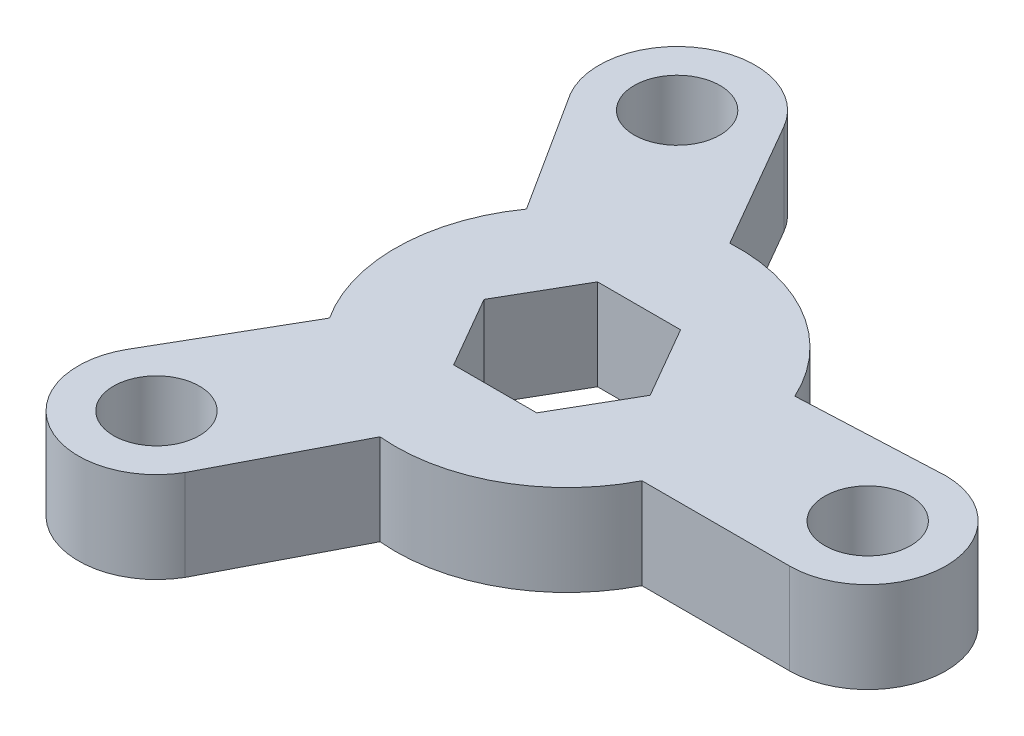
SolidWorks part; units mm, degrees
ref_plane "Front" through (0, 0, 0) normal (0, 0, 1) x (1, 0, 0)
ref_plane "Top" through (0, 0, 0) normal (0, 1, 0) x (1, 0, 0)
ref_plane "Right" through (0, 0, 0) normal (1, 0, 0) x (0, 0, -1)
sketch "Sketch1" plane through (0, 0, 0) normal (0, 1, 0) x (1, 0, 0)
  line L0 (2.5148, 0.2447) -> (13.0148, 0.2447)
  line L1 (2.5148, 0.2447) -> (-2.7352, 9.338)
  line L2 (2.5148, 0.2447) -> (-2.7352, -8.8486)
  line L3 (2.5148, 0.2447) -> (-2.7352, 9.338) construction
  line L10 (2.5148, 0.2447) -> (13.0148, 0.2447) construction
  line L11 (13.0148, -2.4841) -> (7.8583, -2.4841)
  line L12 (13.0148, 2.9736) -> (7.9691, 2.7447)
  line L13 (-5.0985, -7.4841) -> (-2.5203, -3.0185)
  line L14 (-0.372, -10.213) -> (1.9526, -5.7289)
  line L15 (-0.372, 10.7024) -> (2.2062, 6.2368)
  line L16 (-5.0985, 7.9736) -> (-2.3775, 3.7183)
  line L18 (1.0642, -2.2678) -> (3.9654, -2.2678)
  line L19 (3.9654, -2.2678) -> (5.4159, 0.2447)
  line L20 (5.4159, 0.2447) -> (3.9654, 2.7572)
  line L21 (3.9654, 2.7572) -> (1.0642, 2.7572)
  line L22 (1.0642, 2.7572) -> (-0.3864, 0.2447)
  line L23 (-0.3864, 0.2447) -> (1.0642, -2.2678)
  circle A0 centre (-2.7352, 9.338) radius 1.5
  circle A1 centre (13.0148, 0.2447) radius 1.5
  circle A2 centre (-2.7352, -8.8486) radius 1.5
  circle A3 centre (2.5148, 0.2447) radius 2.5125 construction
  arc A4 (-0.372, 10.7024) -> (-5.0985, 7.9736) centre (-2.7352, 9.338) ccw
  circle A5 centre (2.5148, 0.2447) radius 6
  arc A6 (13.0148, -2.4841) -> (13.0148, 2.9736) centre (13.0148, 0.2447) ccw
  arc A7 (-5.0985, -7.4841) -> (-0.372, -10.213) centre (-2.7352, -8.8486) ccw
  point P39 (2.5148, 0.2447)
  dimension "D1" = 3
  dimension "D2" = 120
  dimension "D3" = 3
extrude "Boss-Extrude1" add sketch "Sketch1" along normal blind 3.175
